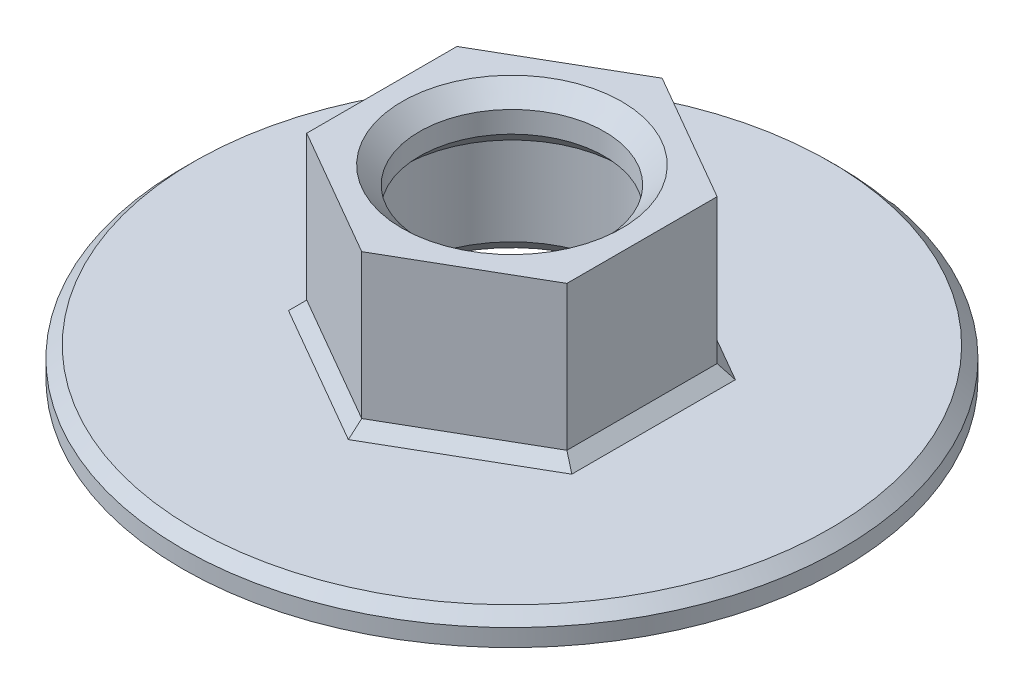
SolidWorks part; units mm, degrees
ref_plane "Front Plane" through (0, 0, 0) normal (0, 0, 1) x (1, 0, 0)
ref_plane "Top Plane" through (0, 0, 0) normal (0, 1, 0) x (1, 0, 0)
ref_plane "Right Plane" through (0, 0, 0) normal (1, 0, 0) x (0, 0, -1)
sketch "Sketch1" plane through (0, 0, 0) normal (0, 1, 0) x (1, 0, 0)
  circle A0 centre (0, 0) radius 27
  circle A1 centre (0, 0) radius 9.675
  dimension "D1" = 54
  dimension "D2" = 19.35
extrude "Boss-Extrude1" add sketch "Sketch1" along normal blind 0.6
sketch "Sketch2" plane through (0, 0.6, 0) normal (0, 1, 0) x (1, 0, 0)
  line L1 (0, 12.9904) -> (-11.25, 6.4952)
  line L2 (-11.25, 6.4952) -> (-11.25, -6.4952)
  line L3 (-11.25, -6.4952) -> (0, -12.9904)
  line L4 (0, -12.9904) -> (11.25, -6.4952)
  line L5 (11.25, -6.4952) -> (11.25, 6.4952)
  line L6 (11.25, 6.4952) -> (0, 12.9904)
  circle A0 centre (0, 0) radius 9.675 construction
  circle A1 centre (0, 0) radius 9.675
  circle A2 centre (0, 0) radius 11.25 construction
  dimension "D1" = 22.5
extrude "Boss-Extrude2" add sketch "Sketch2" along normal blind 13.5
sketch "Sketch3" plane through (0, 14.1, 0) normal (0, 1, 0) x (1, 0, 0)
  circle A0 centre (0, 0) radius 10.0435
  circle A1 centre (0, 0) radius 8
  dimension "D1" = 16
extrude "Boss-Extrude3" add sketch "Sketch3" against normal offset from surface (4.85 mm away) 9.25 up to face at (0, 0, 27)
chamfer "Chamfer1" distance 1.5 angle 45 3 edges at (0, 14.1, 8) (0, 9.25, 8) (0, 0, 9.675)
sketch "Sketch4" plane through (0, 0, 0) normal (0, -1, 0) x (1, 0, 0)
  circle A0 centre (0, 0) radius 28.5
  circle A1 centre (0, 0) radius 25
  dimension "D1" = 50
  dimension "D2" = 57
extrude "Boss-Extrude4" add sketch "Sketch4" along normal blind 1.9 and the other way up to surface other way up to face at (0, 0.6, 27)
chamfer "Chamfer2" distance 1 angle 45 1 edges at (0, 0.6, 28.5)
chamfer "Chamfer3" distance 1 angle 45 6 edges at (5.625, 0.6, 9.7428) (11.25, 0.6, 0) (5.625, 0.6, -9.7428) (-5.625, 0.6, -9.7428) (-11.25, 0.6, 0) (-5.625, 0.6, 9.7428)
sketch "Sketch5" plane through (0, 0, 0) normal (0, 1, 0) x (1, 0, 0)
  arc A0 (3.3368, 24.7763) -> (-3.3368, 24.7763) centre (0, 28.5) ccw
  circle A1 centre (0, 0) radius 28.5 construction
  arc A2 (3.3368, 24.7763) -> (-3.3368, 24.7763) centre (0, 0) ccw
  dimension "D1" = 10
  dimension "D2" = 50
extrude "Cut-Extrude1" cut sketch "Sketch5" against normal blind 8.4
